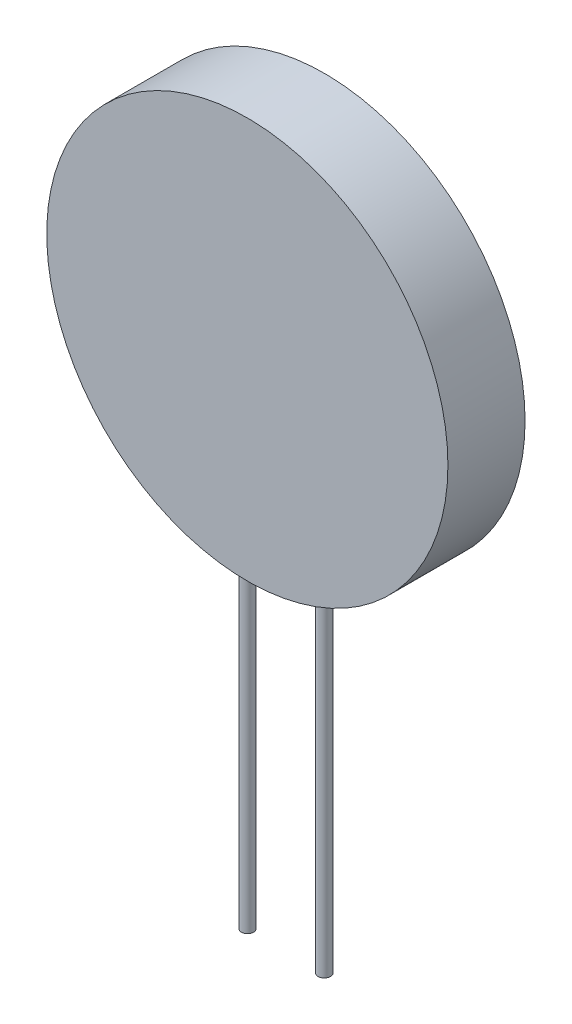
SolidWorks part; units mm, degrees
ref_plane "Front Plane" through (0, 0, 0) normal (0, 0, 1) x (1, 0, 0)
ref_plane "Top Plane" through (0, 0, 0) normal (0, 1, 0) x (1, 0, 0)
ref_plane "Right Plane" through (0, 0, 0) normal (1, 0, 0) x (0, 0, -1)
sketch "Sketch1" plane through (0, 0, 0) normal (0, 0, 1) x (1, 0, 0)
  circle A0 centre (0, 0) radius 13
  dimension "D1" = 26
extrude "Boss-Extrude1" add sketch "Sketch1" along normal mid plane 5
sketch "Sketch2" plane through (0, 0, 0) normal (0, 0, 1) x (1, 0, 0)
  line L0 (-2.5, 0) -> (-2.5, -35)
  dimension "D1" = 2.5
  dimension "D2" = 35
  dimension "D3" = 0
sketch "Sketch3" plane through (0, 0, 0) normal (0, 1, 0) x (1, 0, 0)
  circle A0 centre (-2.4896, 0) radius 0.4
  dimension "D1" = 0.8
sweep "Sweep1" add profiles "Sketch3" path "Sketch2"
mirror "Mirror1" about plane through (0, 0, 0) normal (1, 0, 0) of "Sweep1"
